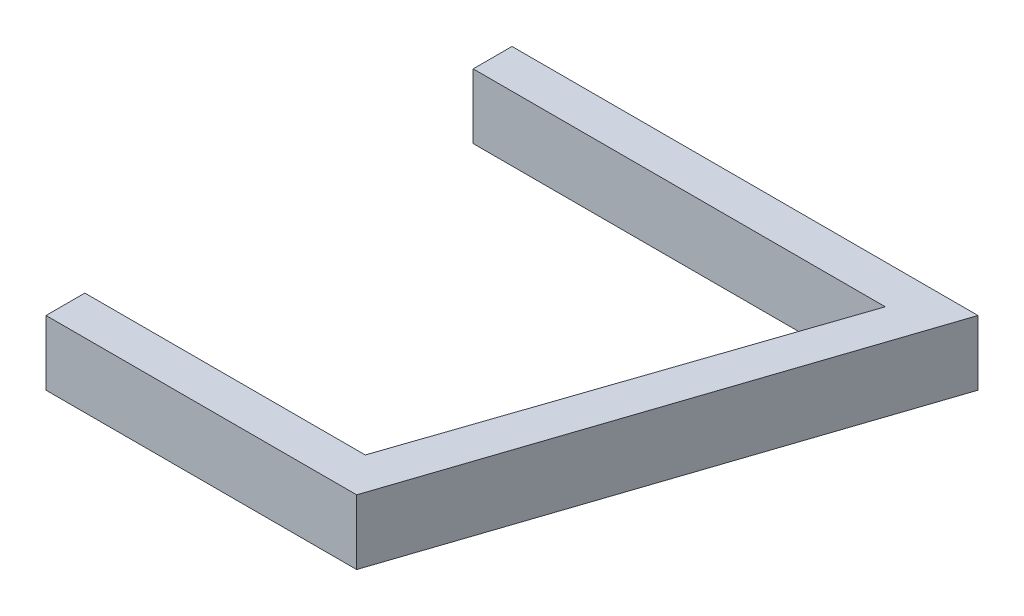
SolidWorks part; units mm, degrees
ref_plane "Front Plane" through (0, 0, 0) normal (0, 0, 1) x (1, 0, 0)
ref_plane "Top Plane" through (0, 0, 0) normal (0, 1, 0) x (1, 0, 0)
ref_plane "Right Plane" through (0, 0, 0) normal (1, 0, 0) x (0, 0, -1)
sketch "Sketch1" plane through (0, 0, 0) normal (0, 1, 0) x (1, 0, 0)
  line L0 (-228.6, 0) -> (228.6, 0)
  line L1 (-228.6, 0) -> (-228.6, -457.2) construction
  line L2 (-228.6, -457.2) -> (76.2, -457.2)
  line L3 (76.2, -457.2) -> (228.6, 0)
  line L4 (-228.6, 0) -> (-228.6, -38.1)
  line L5 (-228.6, -457.2) -> (-228.6, -419.1)
  line L6 (-228.6, -38.1) -> (399.2088, -38.1) construction
  line L7 (-228.6, -419.1) -> (435.0265, -419.1) construction
  line L8 (76.2, -457.2) -> (76.2, 0) construction
  line L9 (84.6667, -431.8) -> (46.5667, -419.1) construction
  line L10 (-228.6, -419.1) -> (46.5667, -419.1)
  line L11 (175.7391, -38.1) -> (46.5667, -419.1)
  line L12 (-228.6, -38.1) -> (175.7391, -38.1)
  line L13 (211.8839, -50.1483) -> (175.7391, -38.1) construction
  point P2 (0, 0)
  point P12 (85.2838, -429.9486)
  point P13 (175.8085, -32.0441)
  point P16 (46.5667, -419.1)
  point P18 (33.7556, -425.191)
  point P19 (212.454, -48.438)
  point P20 (177.2396, -37.6784)
  point P21 (50.059, -419.0712)
  dimension "D1" = 457.2
  dimension "D2" = 457.2
  dimension "D3" = 304.8
  dimension "D4" = 38.1
  dimension "D5" = 38.1
  dimension "D6" = 38.1
  dimension "D7" = 90
  dimension "D8" = 38.1
  dimension "D9" = 90
extrude "Boss-Extrude1" add sketch "Sketch1" along normal blind 63.5
